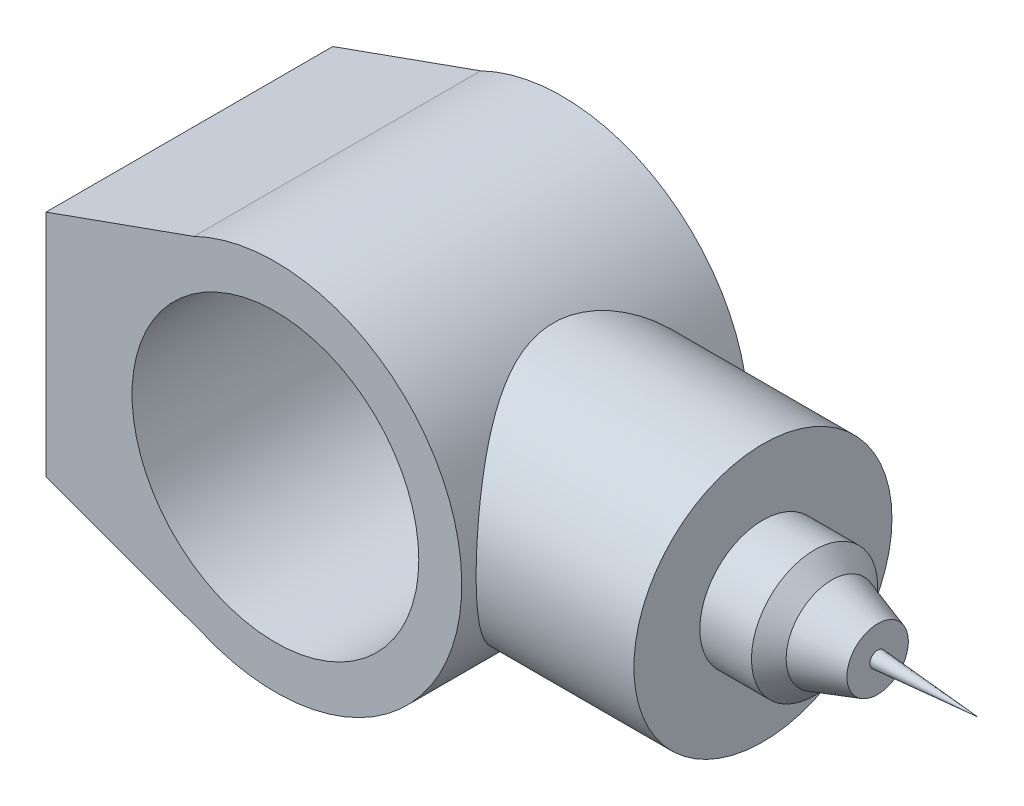
SolidWorks part; units mm, degrees
ref_plane "Front Plane" through (0, 0, 0) normal (0, 0, 1) x (1, 0, 0)
ref_plane "Top Plane" through (0, 0, 0) normal (0, 1, 0) x (1, 0, 0)
ref_plane "Right Plane" through (0, 0, 0) normal (1, 0, 0) x (0, 0, -1)
sketch "Sketch1" plane through (0, 0, 0) normal (0, 0, 1) x (1, 0, 0)
  line L0 (-800, 400) -> (-800, -400)
  line L1 (-800, 400) -> (-284.326, 584.5158)
  line L2 (-800, -400) -> (-256.3436, -597.3173)
  circle A0 centre (0, 0) radius 500
  arc A1 (-256.3436, -597.3173) -> (-284.326, 584.5158) centre (0, 0) ccw
  point P7 (-800, 0)
  dimension "D1" = 1000
  dimension "D2" = 1300
  dimension "D3" = 800
  dimension "D4" = 800
extrude "Boss-Extrude1" add sketch "Sketch1" along normal mid plane 1000
ref_plane "Plane1" through (1200, 0, 0) normal (1, 0, 0) x (0, 0, -1)
sketch "Sketch2" plane through (1200, 0, 0) normal (1, 0, 0) x (0, 0, -1)
  circle A0 centre (0, 0) radius 450
  dimension "D1" = 900
extrude "Boss-Extrude2" add sketch "Sketch2" against normal up to next
sketch "Sketch3" plane through (0, 0, 0) normal (0, 0, 1) x (1, 0, 0)
  line L0 (0, 0) -> (2269.9254, 0) construction
  line L1 (1200, 0) -> (1200, -220)
  line L2 (1200, -450) -> (1200, 450) construction
  line L3 (1200, -220) -> (1380, -220)
  line L4 (1380, -220) -> (1440, -159.0567)
  line L5 (1440, -159.0567) -> (1600, -107.0696)
  line L6 (1600, -107.0696) -> (1600, -27.0696)
  line L7 (1600, -27.0696) -> (1950, 0)
  line L8 (1950, 0) -> (1200, 0)
  dimension "D1" = 750
  dimension "D2" = 350
  dimension "D3" = 80
  dimension "D4" = 160
  dimension "D5" = 180
  dimension "D6" = 85.5224
  dimension "D7" = 220
  dimension "D8" = 18
revolve "Revolve2" add sketch "Sketch3" angle 360 about L0
